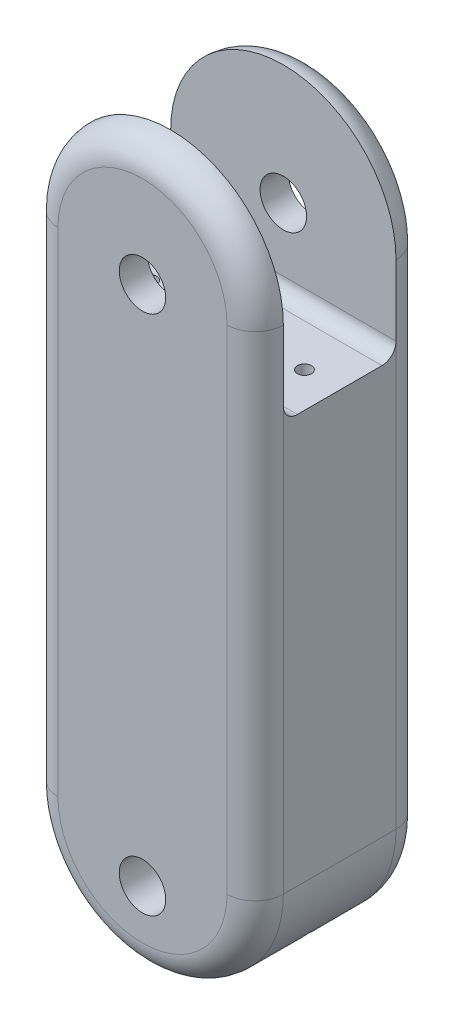
SolidWorks part; units mm, degrees
ref_plane "Front Plane" through (0, 0, 0) normal (0, 0, 1) x (1, 0, 0)
ref_plane "Top Plane" through (0, 0, 0) normal (0, 1, 0) x (1, 0, 0)
ref_plane "Right Plane" through (0, 0, 0) normal (1, 0, 0) x (0, 0, -1)
sketch "Sketch2" plane through (0, 0, 0) normal (0, 0, 1) x (1, 0, 0)
  line L0 (0, -17.5) -> (0, 17.5) construction
  line L1 (-8, -17.5) -> (-8, 17.5)
  line L2 (8, -17.5) -> (8, 17.5)
  arc A0 (-8, -17.5) -> (8, -17.5) centre (0, -17.5) ccw
  arc A1 (8, 17.5) -> (-8, 17.5) centre (0, 17.5) ccw
  point P2 (0, 0)
  dimension "D2" = 8
  dimension "D1" = 35
extrude "Boss-Extrude1" add sketch "Sketch2" along normal blind 12
sketch "Sketch3" plane through (8, 0, 0) normal (1, 0, 0) x (0, 0, -1)
  line L1 (-10, 11.5) -> (-2, 11.5)
  line L2 (-10, 11.5) -> (-10, 25.5)
  line L3 (-10, 25.5) -> (-2, 25.5)
  line L4 (-2, 11.5) -> (-2, 25.5)
  line L5 (0, 25.5) -> (-12, 25.5) construction
  line L7 (-1000, 0) -> (49000, 0) construction
  line L12 (0, 17.5) -> (0, 25.5) construction
  dimension "D1" = 8
  dimension "D2" = 2
  dimension "D3" = 14
fillet "Fillet1" radius 2 8 edges at (-8, 0, 12) (0, 25.5, 12) (8, 0, 12) (0, -25.5, 12) (8, 0, 0) (0, 25.5, 0) (-8, 0, 0) (0, -25.5, 0)
extrude "Cut-Extrude1" cut sketch "Sketch3" against normal through all
fillet "Fillet5" radius 1 2 edges at (0, 11.5, 2) (0, 11.5, 10)
sketch "Sketch4" plane through (0, 0, 12) normal (0, 0, 1) x (1, 0, 0)
  circle A0 centre (0, 17) radius 1.65
  circle A1 centre (0, -20) radius 1.65
  dimension "D1" = 3.3
  dimension "D2" = 3.3
  dimension "D3" = 37
  dimension "D4" = 20
extrude "Cut-Extrude2" cut sketch "Sketch4" against normal through all
sketch "Sketch5" plane through (0, 11.5, 0) normal (0, 1, 0) x (1, 0, 0)
  line L0 (-8, -9) -> (-8, -3) construction
  circle A0 centre (-1, -6) radius 0.5
  circle A1 centre (1, -6) radius 0.5
  point P7 (-8, -6)
  dimension "D1" = 1
  dimension "D2" = 1
  dimension "D3" = 2
  dimension "D4" = 1
ref_plane "Plane1" through (0, -25.5, 0) normal (0, -1, 0) x (-1, 0, 0)
sketch "Sketch6" plane through (0, -25.5, 0) normal (0, -1, 0) x (-1, 0, 0)
  circle A0 centre (-5.5, -6) radius 0.5
  circle A1 centre (5.5, -6) radius 0.5
  dimension "D1" = 1
  dimension "D2" = 4.5
  dimension "D3" = 4.5
extrude "Cut-Extrude3" cut sketch "Sketch6" against normal through all
